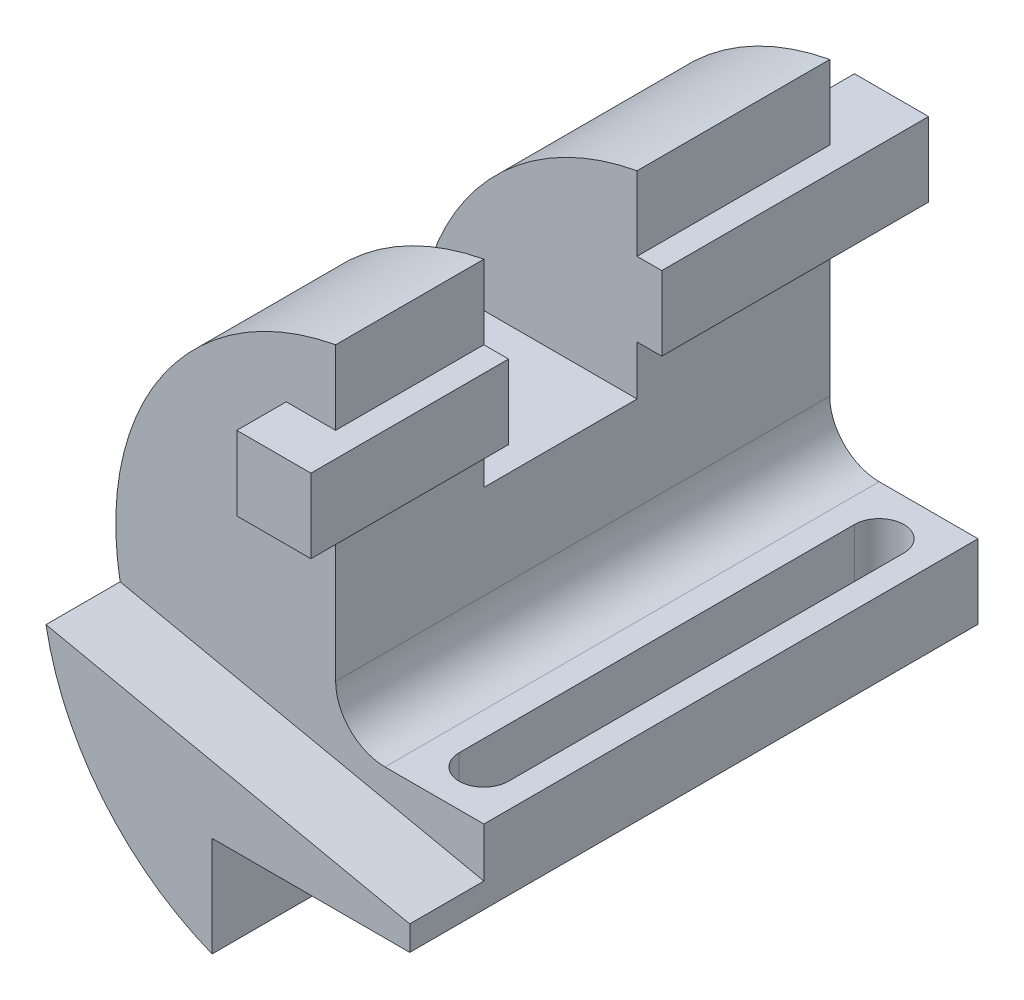
SolidWorks part; units mm, degrees
material "1060 Alloy"
ref_plane "Front Plane" through (0, 0, 0) normal (0, 0, 1) x (1, 0, 0)
ref_plane "Top Plane" through (0, 0, 0) normal (0, 1, 0) x (1, 0, 0)
ref_plane "Right Plane" through (0, 0, 0) normal (1, 0, 0) x (0, 0, -1)
sketch "Sketch1" plane through (0, 0, 0) normal (0, 0, 1) x (1, 0, 0)
  line L0 (0, -46.0189) -> (0, 40.4717) construction
  line L1 (-39.3962, 0) -> (40.4151, 0) construction
  line L2 (-10, 53.5747) -> (-10, -5.4253)
  line L3 (0, -15.4253) -> (20, -15.4253)
  line L4 (20, -15.4253) -> (20, -30.4253)
  line L5 (20, -30.4253) -> (-20, -30.4253)
  line L6 (-20, -30.4253) -> (-20, -50.6976)
  arc A0 (-10, 53.5747) -> (-20, -50.6976) centre (0, 0) ccw
  arc A1 (-10, -5.4253) -> (0, -15.4253) centre (0, -5.4253) ccw
  dimension "D5" = 10
  dimension "D6" = 54.5
  dimension "D1" = 15
  dimension "D2" = 40
  dimension "D3" = 69
  dimension "D4" = 10
  dimension "D7" = 20
extrude "Boss-Extrude1" add sketch "Sketch1" against normal blind 100
sketch "Sketch2" plane through (0, 0, 0) normal (0, 0, 1) x (1, 0, 0)
  line L0 (20, -25.4253) -> (20, -30.4253)
  line L1 (20, -30.4253) -> (20, -15.4253) construction
  line L2 (20, -30.4253) -> (-20, -30.4253)
  line L3 (-20, -30.4253) -> (-20, -50.6976)
  line L4 (20, -25.4253) -> (-53.6157, -9.7778)
  arc A1 (-10, 53.5747) -> (-20, -50.6976) centre (0, 0) ccw construction
  arc A2 (-20, -50.6976) -> (-53.6157, -9.7778) centre (0, 0) cw
  dimension "D1" = 78
  dimension "D2" = 5
extrude "Boss-Extrude2" add sketch "Sketch2" along normal blind 15
sketch "Sketch3" plane through (0, 0, 0) normal (0, 0, 1) x (1, 0, 0)
  line L0 (-10, -5.4253) -> (-10, 53.5747) construction
  line L1 (-20, 38.5747) -> (-5, 38.5747)
  line L2 (-20, 38.5747) -> (-20, 23.5747)
  line L3 (-20, 23.5747) -> (-5, 23.5747)
  line L4 (-5, 38.5747) -> (-5, 23.5747)
  dimension "D1" = 5
  dimension "D2" = 15
  dimension "D3" = 15
  dimension "D4" = 15
extrude "Boss-Extrude3" add sketch "Sketch3" against normal blind 30
sketch "Sketch4" plane through (0, 0, 0) normal (0, 0, 1) x (1, 0, 0)
  line L1 (-5, 38.5747) -> (-20, 38.5747)
  line L2 (-5, 38.5747) -> (-5, 23.5747)
  line L3 (-5, 23.5747) -> (-20, 23.5747)
  line L4 (-20, 38.5747) -> (-20, 23.5747)
  dimension "D1" = 15
  dimension "D2" = 15
extrude "Boss-Extrude4" add sketch "Sketch4" along normal blind 10
sketch "Sketch7" plane through (-10, 0, 0) normal (1, 0, 0) x (0, 0, -1)
  line L0 (100, 53.5747) -> (0, 53.5747) construction
  line L1 (30, 53.5747) -> (61, 53.5747)
  line L2 (30, 53.5747) -> (30, 13.5747)
  line L3 (30, 13.5747) -> (61, 13.5747)
  line L4 (61, 53.5747) -> (61, 13.5747)
  dimension "D1" = 31
  dimension "D2" = 40
extrude "Cut-Extrude2" cut sketch "Sketch7" against normal through all
sketch "Sketch8" plane through (0, 0, -100) normal (0, 0, -1) x (-1, 0, 0)
  line L1 (5, 38.5747) -> (20, 38.5747)
  line L2 (5, 38.5747) -> (5, 23.5747)
  line L3 (5, 23.5747) -> (20, 23.5747)
  line L4 (20, 38.5747) -> (20, 23.5747)
  dimension "D1" = 15
  dimension "D2" = 15
extrude "Boss-Extrude5" add sketch "Sketch8" against normal up to surface (39 mm away) up to face at (-26.2041, 28.9865, -61)
sketch "Sketch9" plane through (0, 0, -100) normal (0, 0, -1) x (-1, 0, 0)
  line L1 (5, 38.5747) -> (20, 38.5747)
  line L2 (5, 38.5747) -> (5, 23.5747)
  line L3 (5, 23.5747) -> (20, 23.5747)
  line L4 (20, 38.5747) -> (20, 23.5747)
  dimension "D1" = 15
  dimension "D2" = 15
extrude "Boss-Extrude6" add sketch "Sketch9" along normal blind 15
sketch "Sketch10" plane through (0, -15.4253, 0) normal (0, 1, 0) x (1, 0, 0)
  line L0 (5, 10) -> (5, 90)
  line L1 (15, 10) -> (15, 90)
  line L2 (20, 0) -> (-53.6157, 0) construction
  line L4 (20, 100) -> (20, 0) construction
  arc A0 (5, 90) -> (15, 90) centre (10, 90) cw
  arc A1 (5, 10) -> (15, 10) centre (10, 10) ccw
  dimension "D1" = 10
  dimension "D2" = 80
  dimension "D3" = 10
  dimension "D4" = 10
extrude "Cut-Extrude4" cut sketch "Sketch10" against normal through all
equation "\"A\" = 49.5"
equation "\"B\" = 53"
equation "\"C\"= 38"
